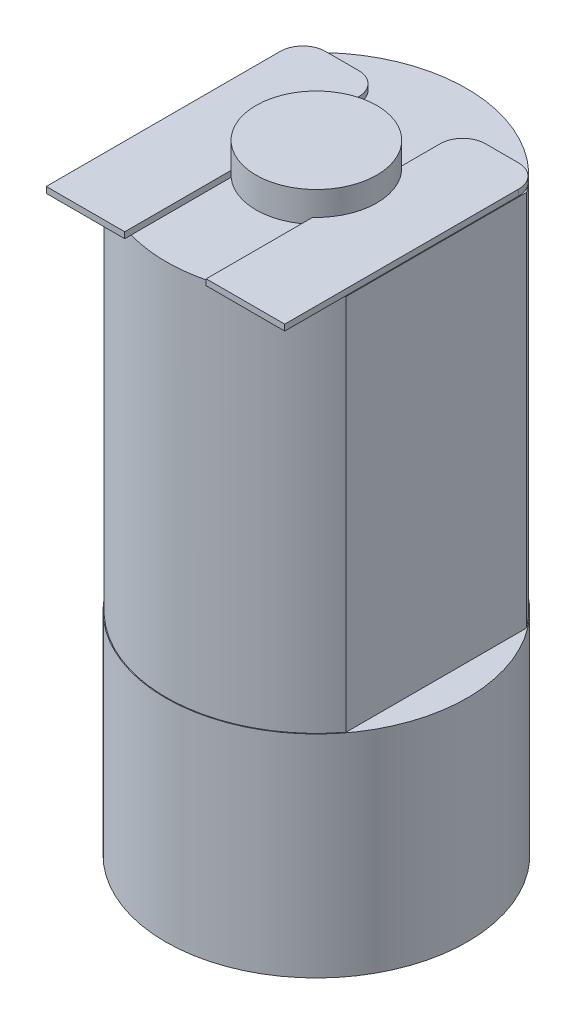
SolidWorks part; units mm, degrees
ref_plane "Front Plane" through (0, 0, 0) normal (0, 0, 1) x (1, 0, 0)
ref_plane "Top Plane" through (0, 0, 0) normal (0, 1, 0) x (1, 0, 0)
ref_plane "Right Plane" through (0, 0, 0) normal (1, 0, 0) x (0, 0, -1)
sketch "Sketch2" plane through (0, 0, 0) normal (0, 1, 0) x (1, 0, 0)
  circle A0 centre (0, 0) radius 5
  dimension "D1" = 10
extrude "Boss-Extrude1" add sketch "Sketch2" along normal blind 7
sketch "Sketch3" plane through (0, 7, 0) normal (0, 1, 0) x (1, 0, 0)
  line L2 (-3.975, 2.9917) -> (-3.975, -2.9917)
  line L4 (3.975, 2.9917) -> (3.975, -2.9917)
  line L5 (-3.975, 5.437) -> (3.975, -5.437) construction
  line L6 (-3.975, -5.437) -> (3.975, 5.437) construction
  arc A0 (-3.975, -2.9917) -> (3.975, -2.9917) centre (0, 0) ccw
  arc A1 (3.975, 2.9917) -> (-3.975, 2.9917) centre (0, 0) ccw
  point P7 (-4.975, 0)
  dimension "D1" = 9.95
  dimension "D2" = 1
extrude "Boss-Extrude2" add sketch "Sketch3" along normal blind 12.5
sketch "Sketch4" plane through (0, 19.5, 0) normal (0, 1, 0) x (1, 0, 0)
  line L0 (0, -5.9807) -> (0, 5.9807) construction
  line L5 (-3.2, 3.5) -> (-2.1, 3.5)
  line L6 (-3.95, 2.75) -> (-3.95, -5)
  line L7 (-3.95, -5) -> (-1.35, -5)
  line L8 (-1.35, 2.75) -> (-1.35, -5)
  line L9 (-3.95, 3.5) -> (-1.35, -5) construction
  line L10 (-3.95, -5) -> (-1.35, 3.5) construction
  line L11 (3.95, -5) -> (1.35, -5)
  line L12 (1.35, 2.75) -> (1.35, -5)
  line L13 (3.2, 3.5) -> (2.1, 3.5)
  line L14 (3.95, 2.75) -> (3.95, -5)
  arc A0 (-1.35, 2.75) -> (-2.1, 3.5) centre (-2.1, 2.75) ccw
  arc A1 (-3.2, 3.5) -> (-3.95, 2.75) centre (-3.2, 2.75) ccw
  arc A2 (1.35, 2.75) -> (2.1, 3.5) centre (2.1, 2.75) cw
  arc A3 (3.2, 3.5) -> (3.95, 2.75) centre (3.2, 2.75) cw
  point P0 (-2.65, -0.75)
  dimension "D5" = 0.75
  dimension "D1" = 2.6
  dimension "D2" = 2.65
  dimension "D3" = 5
  dimension "D4" = 3.5
extrude "Boss-Extrude3" add sketch "Sketch4" along normal blind 0.2
sketch "Sketch5" plane through (0, 19.5, 0) normal (0, 1, 0) x (1, 0, 0)
  circle A0 centre (0, 0) radius 2
  dimension "D1" = 4
extrude "Boss-Extrude4" add sketch "Sketch5" along normal blind 1
